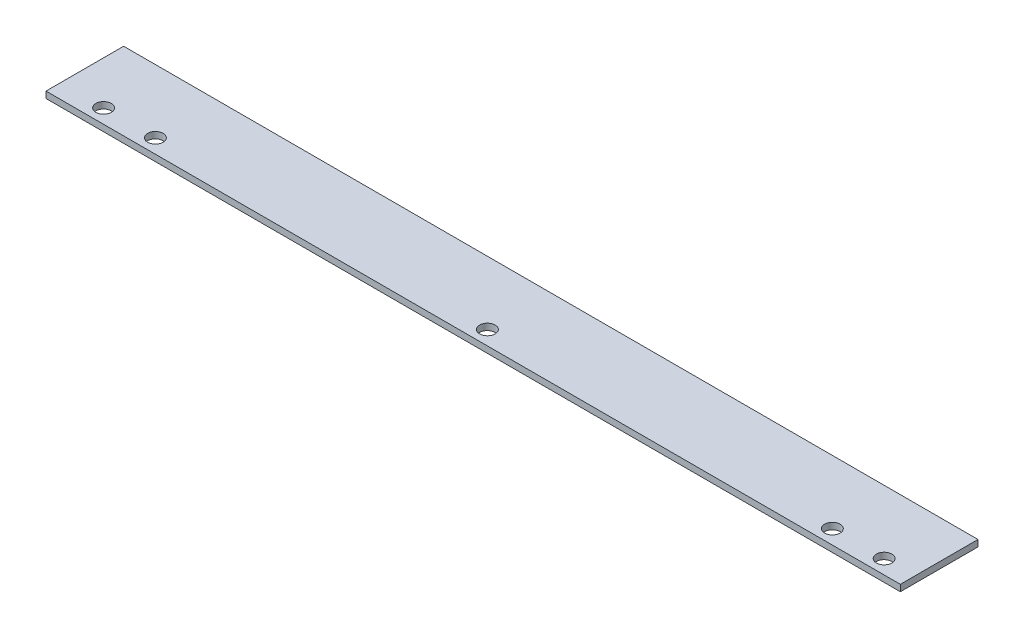
SolidWorks part; units mm, degrees
ref_plane "Front Plane" through (0, 0, 0) normal (0, 0, 1) x (1, 0, 0)
ref_plane "Top Plane" through (0, 0, 0) normal (0, 1, 0) x (1, 0, 0)
ref_plane "Right Plane" through (0, 0, 0) normal (1, 0, 0) x (0, 0, -1)
sketch "Sketch2" plane through (0, 0, 0) normal (0, 1, 0) x (1, 0, 0)
  line L0 (-104.775, -9.525) -> (-104.775, -2.5449) construction
  line L1 (-104.775, -9.525) -> (104.775, -9.525)
  line L2 (-104.775, -9.525) -> (-104.775, 9.525)
  line L3 (-104.775, 9.525) -> (104.775, 9.525)
  line L4 (104.775, -9.525) -> (104.775, 9.525)
  line L5 (-104.775, -9.525) -> (104.775, 9.525) construction
  line L6 (-104.775, 9.525) -> (104.775, -9.525) construction
  point P0 (0, 0)
  dimension "D1" = 19.05
extrude "Boss-Extrude1" add sketch "Sketch2" along normal blind 1.5875
hole_wizard "#6 Clearance Hole1" positions "Sketch3" profile "Sketch4" hole size "#6" standard "ANSI Inch" end condition up to next
sketch "Sketch3" plane through (0, 1.5875, 0) normal (0, 1, 0) x (1, 0, 0)
  line L5 (-94.1372, -7.7494) -> (-94.1372, -4.3204) construction
  line L7 (97.3122, -7.7494) -> (97.3122, -4.3204) construction
  arc A0 (-94.1372, -4.3204) -> (-94.1372, -7.7494) centre (-94.1702, -6.0349) ccw construction
  arc A1 (97.3122, -7.7494) -> (97.3122, -4.3204) centre (97.3452, -6.0349) ccw construction
  point P0 (-94.1372, -6.0349)
  point P2 (0, -6.0349)
  point P4 (97.3122, -6.0349)
  point P35 (97.3122, -6.0349)
  point P37 (-94.1372, -6.0349)
  point P38 (-81.4372, -6.0349)
  point P40 (84.6122, -6.0349)
  dimension "D1" = 12.7
  dimension "D2" = 12.7
sketch "Sketch4" plane through (-94.1372, 1.5875, 6.0349) normal (1, 0, 0) x (0, 0, 1)
  line L0 (0, 0) -> (0, 1.5875)
  line L1 (0, 1.5875) -> (1.8986, 1.5875)
  line L2 (1.8986, 1.5875) -> (1.8986, 0)
  line L5 (1.8986, 0) -> (0, 0)
  line L11 (0, -6.35) -> (0, 107.95) construction
  dimension "Thru Hole Dia." = 3.7973
  dimension "Thru Hole Depth" = 1.5875
